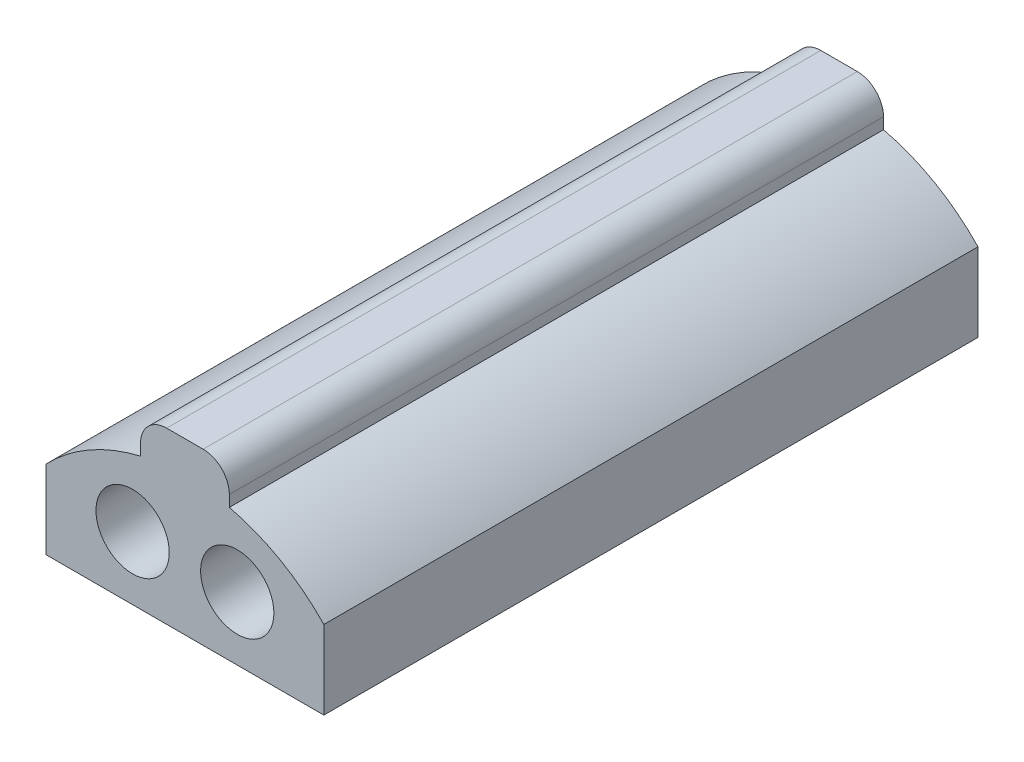
SolidWorks part; units mm, degrees
ref_plane "Front Plane" through (0, 0, 0) normal (0, 0, 1) x (1, 0, 0)
ref_plane "Top Plane" through (0, 0, 0) normal (0, 1, 0) x (1, 0, 0)
ref_plane "Right Plane" through (0, 0, 0) normal (1, 0, 0) x (0, 0, -1)
sketch "Sketch1" plane through (0, 0, 0) normal (0, 0, 1) x (1, 0, 0)
  line L0 (-10.6184, 0) -> (10.6184, 0)
  line L1 (10.6184, 0) -> (10.6184, 6)
  line L2 (3.3956, 10.1368) -> (3.3956, 10.9893)
  line L3 (1.3956, 12.9893) -> (-1.3956, 12.9893)
  line L4 (-3.3956, 10.9893) -> (-3.3956, 10.1368)
  line L5 (-10.6184, 6) -> (-10.6184, 0)
  arc A0 (10.6184, 6) -> (3.3956, 10.1368) centre (0, -4.1656) ccw construction
  arc A3 (-3.3956, 10.1368) -> (-10.6184, 6) centre (0, -4.1656) ccw construction
  arc A4 (10.6184, 6) -> (3.3956, 10.1368) centre (0, -4.1656) ccw
  arc A5 (-3.3956, 10.1368) -> (-10.6184, 6) centre (0, -4.1656) ccw
  arc A6 (1.3956, 12.9893) -> (3.3956, 10.9893) centre (1.3956, 10.9893) cw
  arc A7 (-1.3956, 12.9893) -> (-3.3956, 10.9893) centre (-1.3956, 10.9893) ccw
  point P4 (-3.3956, 16.7981)
  point P6 (-5.4553, 12.9893)
  point P7 (0, 0)
  point P8 (0, -4.1656)
  point P14 (0, 0)
  point P16 (0, 0)
  point P17 (0, 0)
  point P18 (0, 0)
  point P19 (0, 0)
  point P20 (0, -4.1656)
  point P21 (6.8348, 12.9893)
  point P22 (0, 0)
  dimension "D2" = 29.4
  dimension "D5" = 10.1368
  dimension "D6" = 2
  dimension "D1" = 21.2368
  dimension "D3" = 4.1656
  dimension "D4" = 12.9893
extrude "Boss-Extrude1" add sketch "Sketch1" against normal blind 50
sketch "Sketch2" plane through (0, 0, 0) normal (0, 0, 1) x (1, 0, 0)
  line L0 (-10.6184, 0) -> (10.6184, 0) construction
  circle A0 centre (-4, 4.84) radius 2.8
  circle A1 centre (4, 4.84) radius 2.8
  point P7 (0, 0)
  dimension "D3" = 5.6
  dimension "D1" = 4
  dimension "D2" = 4
  dimension "D4" = 4.84
extrude "Cut-Extrude1" cut sketch "Sketch2" against normal through all
equation "\"D2@Sketch2\"=\"D1@Sketch2\""
